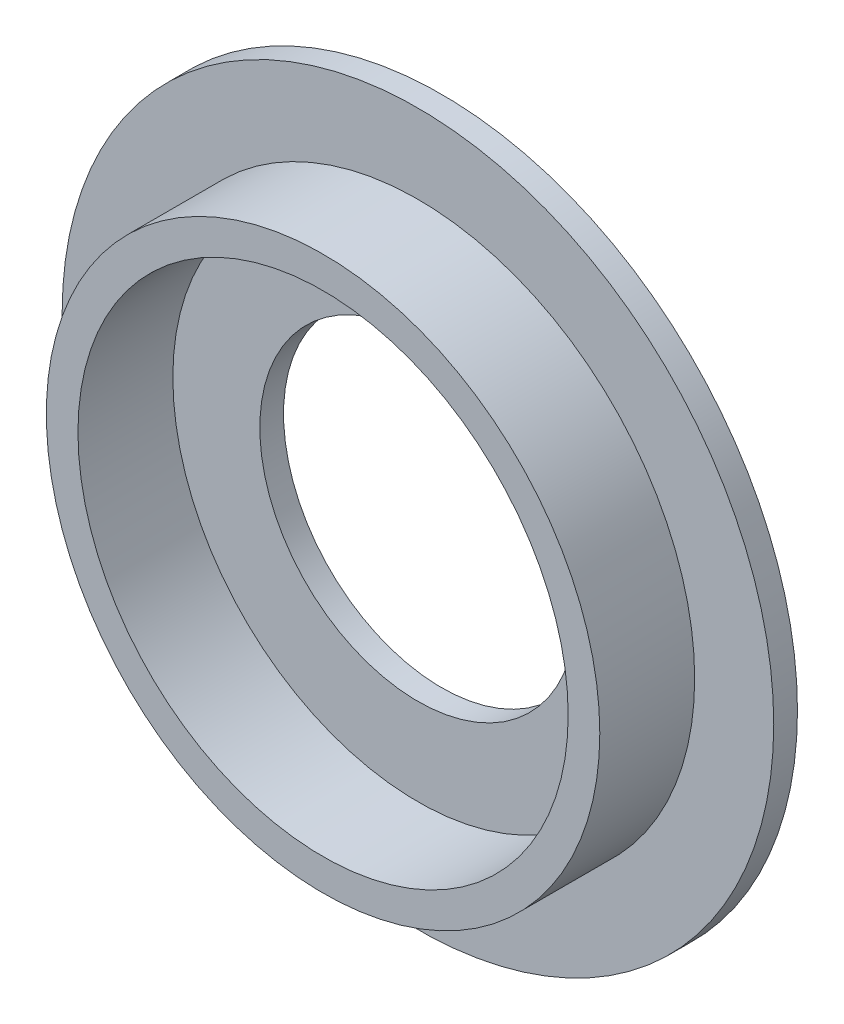
SolidWorks part; units mm, degrees
ref_plane "Front Plane" through (0, 0, 0) normal (0, 0, 1) x (1, 0, 0)
ref_plane "Top Plane" through (0, 0, 0) normal (0, 1, 0) x (1, 0, 0)
ref_plane "Right Plane" through (0, 0, 0) normal (1, 0, 0) x (0, 0, -1)
sketch "Sketch1" plane through (0, 0, 0) normal (0, 0, 1) x (1, 0, 0)
  circle A0 centre (0, 0) radius 45
  dimension "D1" = 90
extrude "Boss-Extrude3" add sketch "Sketch1" along normal blind 3
sketch "Sketch2" plane through (0, 0, 3) normal (0, 0, 1) x (1, 0, 0)
  circle A0 centre (0, 0) radius 35
  dimension "D1" = 70
extrude "Boss-Extrude4" add sketch "Sketch2" along normal blind 12
sketch "Sketch3" plane through (0, 0, 15) normal (0, 0, 1) x (1, 0, 0)
  circle A0 centre (0, 0) radius 31
  dimension "D1" = 62
extrude "Cut-Extrude2" cut sketch "Sketch3" against normal blind 12
sketch "Sketch4" plane through (0, 0, 3) normal (0, 0, 1) x (1, 0, 0)
  circle A0 centre (0, 0) radius 20
  dimension "D1" = 40
extrude "Cut-Extrude3" cut sketch "Sketch4" against normal blind 8
